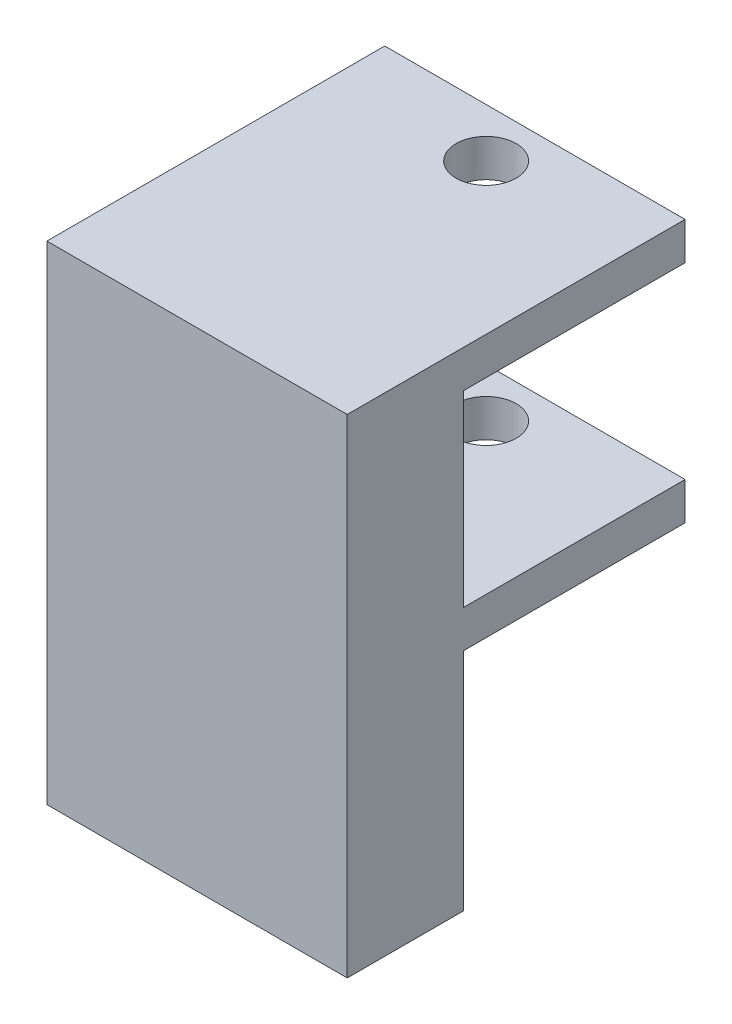
SolidWorks part; units mm, degrees
ref_plane "Plano frontal" through (0, 0, 0) normal (0, 0, 1) x (1, 0, 0)
ref_plane "Plano superior" through (0, 0, 0) normal (0, 1, 0) x (1, 0, 0)
ref_plane "Plano direito" through (0, 0, 0) normal (1, 0, 0) x (0, 0, -1)
sketch "Esboço1" plane through (0, 0, 0) normal (0, 1, 0) x (1, 0, 0)
  line L1 (0, 0) -> (40, 0)
  line L2 (0, 0) -> (0, 15.5)
  line L3 (0, 15.5) -> (40, 15.5)
  line L4 (40, 0) -> (40, 15.5)
  dimension "D1" = 40
  dimension "D2" = 15.5
extrude "Ressalto-extrusão1" add sketch "Esboço1" along normal blind 30
sketch "Esboço2" plane through (0, 0, 0) normal (0, -1, 0) x (1, 0, 0)
  line L0 (0, 0) -> (40, 0) construction
  line L1 (4, -4) -> (11, -4)
  line L2 (4, -4) -> (4, -11)
  line L3 (4, -11) -> (11, -11)
  line L4 (11, -4) -> (11, -11)
  line L5 (4, -4) -> (11, -11) construction
  line L6 (4, -11) -> (11, -4) construction
  line L7 (29, -4) -> (36, -4)
  line L8 (29, -4) -> (29, -11)
  line L9 (29, -11) -> (36, -11)
  line L10 (36, -4) -> (36, -11)
  line L11 (29, -4) -> (36, -11) construction
  line L12 (29, -11) -> (36, -4) construction
  line L13 (0, -15.5) -> (0, 0) construction
  line L15 (40, 0) -> (40, -15.5) construction
  point P0 (7.5, -7.5)
  point P5 (32.5, -7.5)
  point P16 (40, -6.6077)
  dimension "D1" = 7
  dimension "D2" = 7
  dimension "D3" = 7
  dimension "D4" = 7
  dimension "D5" = 7.5
  dimension "D6" = 7.5
  dimension "D7" = 7.5
  dimension "D8" = 7.5
extrude "Corte-extrusão1" cut sketch "Esboço2" against normal blind 12
sketch "Esboço5" plane through (0, 30, 0) normal (0, 1, 0) x (1, 0, 0)
  line L1 (0, 0) -> (40, 0)
  line L2 (0, 0) -> (0, 45)
  line L3 (0, 45) -> (40, 45)
  line L4 (40, 0) -> (40, 45)
  dimension "D1" = 45
  dimension "D2" = 40
extrude "Ressalto-extrusão2" add sketch "Esboço5" along normal blind 5
sketch "Esboço6" plane through (0, 35, 0) normal (0, 1, 0) x (1, 0, 0)
  line L1 (0, 0) -> (40, 0)
  line L2 (0, 0) -> (0, 15.5)
  line L3 (0, 15.5) -> (40, 15.5)
  line L4 (40, 0) -> (40, 15.5)
  dimension "D1" = 40
  dimension "D2" = 15.5
extrude "Ressalto-extrusão3" add sketch "Esboço6" along normal blind 25
sketch "Esboço7" plane through (0, 60, 0) normal (0, 1, 0) x (1, 0, 0)
  line L1 (0, 0) -> (40, 0)
  line L2 (0, 0) -> (0, 45)
  line L3 (0, 45) -> (40, 45)
  line L4 (40, 0) -> (40, 45)
extrude "Ressalto-extrusão4" add sketch "Esboço7" along normal blind 5
sketch "Esboço8" plane through (0, 65, 0) normal (0, 1, 0) x (1, 0, 0)
  line L0 (20, -2.5188) -> (20, 46.7663) construction
  line L1 (40, 0) -> (40, 45) construction
  line L2 (40, 45) -> (0, 45) construction
  circle A0 centre (20, 38.5) radius 4
  dimension "D2" = 6.5
  dimension "D3" = 8
  dimension "D1" = 20
extrude "Corte-extrusão2" cut sketch "Esboço8" against normal through all
